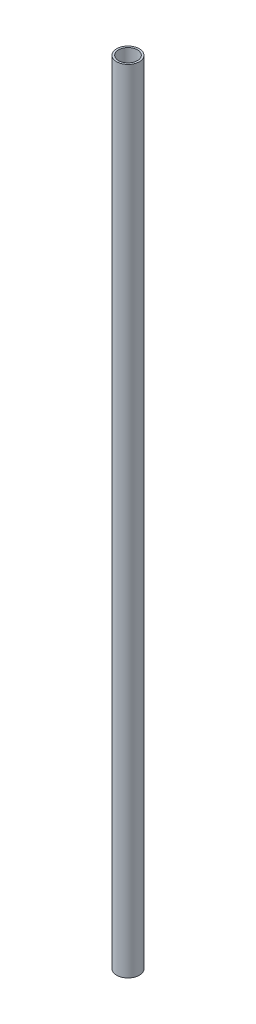
SolidWorks part; units mm, degrees
material "Thornel Mat VMA"
ref_plane "Front Plane" through (0, 0, 0) normal (0, 0, 1) x (1, 0, 0)
ref_plane "Top Plane" through (0, 0, 0) normal (0, 1, 0) x (1, 0, 0)
ref_plane "Right Plane" through (0, 0, 0) normal (1, 0, 0) x (0, 0, -1)
sketch "Sketch1" plane through (0, 0, 0) normal (0, 1, 0) x (1, 0, 0)
  circle A0 centre (0, 0) radius 6
  circle A1 centre (0, 0) radius 5
extrude "Boss-Extrude1" add sketch "Sketch1" along normal blind 420
